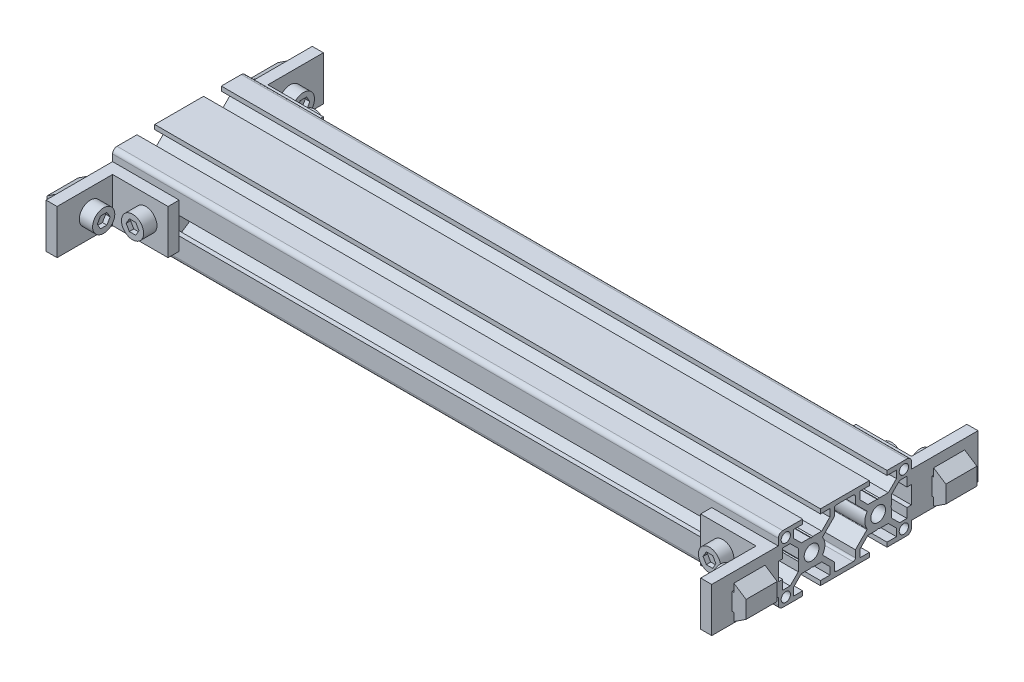
SolidWorks part; units mm, degrees
ref_plane "Front Plane" through (0, 0, 0) normal (0, 0, 1) x (1, 0, 0)
ref_plane "Top Plane" through (0, 0, 0) normal (0, 1, 0) x (1, 0, 0)
ref_plane "Right Plane" through (0, 0, 0) normal (1, 0, 0) x (0, 0, -1)
ref_plane "Plane1" through (300, 0, 0) normal (1, 0, 0) x (0, 0, -1)
ref_plane "Plane2" through (150, 0, 0) normal (1, 0, 0) x (0, 0, -1)
sketch "Sketch1" plane through (0, 0, 0) normal (1, 0, 0) x (0, 0, -1)
  line L0 (4.75, 8.8358) -> (4.75, 12)
  line L1 (3.75, 13) -> (-3.75, 13)
  line L2 (-4.75, 12) -> (-4.75, 8.8358)
  line L3 (-4.75, 8.8358) -> (-9.934, 3.6518)
  line L4 (-9.934, -3.6518) -> (-4.75, -8.8358)
  line L5 (-4.75, -8.8358) -> (-4.75, -12)
  line L6 (-3.75, -13) -> (3.75, -13)
  line L7 (4.75, -12) -> (4.75, -8.8358)
  line L8 (4.75, -8.8358) -> (9.934, -3.6518)
  line L9 (9.934, 3.6518) -> (4.75, 8.8358)
  line L10 (-11, -15) -> (11, -15)
  line L11 (11, -15) -> (11, -13)
  line L12 (11, -13) -> (6.75, -13)
  line L13 (6.75, -13) -> (6.75, -9.6642)
  line L14 (6.75, -9.6642) -> (10.4142, -6)
  line L15 (10.4142, -6) -> (14.4804, -6)
  line L16 (14.4804, -6) -> (15, -5.7)
  line L17 (15, -5.7) -> (15.5196, -6)
  line L18 (15.5196, -6) -> (19.5858, -6)
  line L19 (19.5858, -6) -> (23.25, -9.6642)
  line L20 (23.25, -9.6642) -> (23.25, -13)
  line L21 (23.25, -13) -> (19, -13)
  line L22 (19, -13) -> (19, -15)
  line L23 (19, -15) -> (28, -15)
  line L24 (30, -13) -> (30, -4)
  line L25 (30, -4) -> (28, -4)
  line L26 (28, -4) -> (28, -8.25)
  line L27 (28, -8.25) -> (24.6642, -8.25)
  line L28 (24.6642, -8.25) -> (21, -4.5858)
  line L29 (21, -4.5858) -> (21, -0.5196)
  line L30 (21, -0.5196) -> (20.7, 0)
  line L31 (20.7, 0) -> (21, 0.5196)
  line L32 (21, 0.5196) -> (21, 4.5858)
  line L33 (21, 4.5858) -> (24.6642, 8.25)
  line L34 (24.6642, 8.25) -> (28, 8.25)
  line L35 (28, 8.25) -> (28, 4)
  line L36 (28, 4) -> (30, 4)
  line L37 (30, 4) -> (30, 13)
  line L38 (28, 15) -> (19, 15)
  line L39 (19, 15) -> (19, 13)
  line L40 (19, 13) -> (23.25, 13)
  line L41 (23.25, 13) -> (23.25, 9.6642)
  line L42 (23.25, 9.6642) -> (19.5858, 6)
  line L43 (19.5858, 6) -> (15.5196, 6)
  line L44 (15.5196, 6) -> (15, 5.7)
  line L45 (15, 5.7) -> (14.4804, 6)
  line L46 (14.4804, 6) -> (10.4142, 6)
  line L47 (10.4142, 6) -> (6.75, 9.6642)
  line L48 (6.75, 9.6642) -> (6.75, 13)
  line L49 (6.75, 13) -> (11, 13)
  line L50 (11, 13) -> (11, 15)
  line L51 (11, 15) -> (-11, 15)
  line L52 (-11, 15) -> (-11, 13)
  line L53 (-11, 13) -> (-6.75, 13)
  line L54 (-6.75, 13) -> (-6.75, 9.6642)
  line L55 (-6.75, 9.6642) -> (-10.4142, 6)
  line L56 (-10.4142, 6) -> (-14.4804, 6)
  line L57 (-14.4804, 6) -> (-15, 5.7)
  line L58 (-15, 5.7) -> (-15.5196, 6)
  line L59 (-15.5196, 6) -> (-19.5858, 6)
  line L60 (-19.5858, 6) -> (-23.25, 9.6642)
  line L61 (-23.25, 9.6642) -> (-23.25, 13)
  line L62 (-23.25, 13) -> (-19, 13)
  line L63 (-19, 13) -> (-19, 15)
  line L64 (-19, 15) -> (-28, 15)
  line L65 (-30, 13) -> (-30, 4)
  line L66 (-30, 4) -> (-28, 4)
  line L67 (-28, 4) -> (-28, 8.25)
  line L68 (-28, 8.25) -> (-24.6642, 8.25)
  line L69 (-24.6642, 8.25) -> (-21, 4.5858)
  line L70 (-21, 4.5858) -> (-21, 0.5196)
  line L71 (-21, 0.5196) -> (-20.7, 0)
  line L72 (-20.7, 0) -> (-21, -0.5196)
  line L73 (-21, -0.5196) -> (-21, -4.5858)
  line L74 (-21, -4.5858) -> (-24.6642, -8.25)
  line L75 (-24.6642, -8.25) -> (-28, -8.25)
  line L76 (-28, -8.25) -> (-28, -4)
  line L77 (-28, -4) -> (-30, -4)
  line L78 (-30, -4) -> (-30, -13)
  line L79 (-28, -15) -> (-19, -15)
  line L80 (-19, -15) -> (-19, -13)
  line L81 (-19, -13) -> (-23.25, -13)
  line L82 (-23.25, -13) -> (-23.25, -9.6642)
  line L83 (-23.25, -9.6642) -> (-19.5858, -6)
  line L84 (-19.5858, -6) -> (-15.5196, -6)
  line L85 (-15.5196, -6) -> (-15, -5.7)
  line L86 (-15, -5.7) -> (-14.4804, -6)
  line L87 (-14.4804, -6) -> (-10.4142, -6)
  line L88 (-10.4142, -6) -> (-6.75, -9.6642)
  line L89 (-6.75, -9.6642) -> (-6.75, -13)
  line L90 (-6.75, -13) -> (-11, -13)
  line L91 (-11, -13) -> (-11, -15)
  arc A0 (28, -15) -> (30, -13) centre (28, -13) ccw
  arc A1 (30, 13) -> (28, 15) centre (28, 13) ccw
  arc A2 (-28, 15) -> (-30, 13) centre (-28, 13) ccw
  arc A3 (-30, -13) -> (-28, -15) centre (-28, -13) ccw
  circle A4 centre (-26.6, -11.6) radius 2.1
  circle A5 centre (-26.6, 11.6) radius 2.1
  circle A6 centre (-15, 0) radius 3.3235
  circle A7 centre (26.6, -11.6) radius 2.1
  circle A8 centre (15, 0) radius 3.3235
  circle A9 centre (26.6, 11.6) radius 2.1
  arc A10 (4.75, 12) -> (3.75, 13) centre (3.75, 12) ccw
  arc A11 (-3.75, 13) -> (-4.75, 12) centre (-3.75, 12) ccw
  arc A12 (-9.934, 3.6518) -> (-9.9732, 3.2759) centre (-9.7219, 3.4397) ccw
  arc A13 (-9.9732, -3.2759) -> (-9.9732, 3.2759) centre (-15, 0) ccw
  arc A14 (-9.9732, -3.2759) -> (-9.934, -3.6518) centre (-9.7219, -3.4397) ccw
  arc A15 (-4.75, -12) -> (-3.75, -13) centre (-3.75, -12) ccw
  arc A16 (3.75, -13) -> (4.75, -12) centre (3.75, -12) ccw
  arc A17 (9.934, -3.6518) -> (9.9732, -3.2759) centre (9.7219, -3.4397) ccw
  arc A18 (9.9732, 3.2759) -> (9.9732, -3.2759) centre (15, 0) ccw
  arc A19 (9.9732, 3.2759) -> (9.934, 3.6518) centre (9.7219, 3.4397) ccw
  point P106 (0, 0)
extrude "Boss-Extrude1" add sketch "Sketch1" along normal up to surface (300 mm away) up to plane "Plane1"
sketch "Sketch2" plane through (0, 0, 0) normal (0, 1, 0) x (1, 0, 0)
  line L0 (0, 60) -> (0, 30)
  line L1 (0, 30) -> (30, 30)
  line L2 (30, 30) -> (30, 35)
  line L3 (30, 35) -> (5, 35)
  line L4 (5, 35) -> (5, 60)
  line L5 (5, 60) -> (0, 60)
  dimension "FIX_1" = 30
  dimension "FIX_2" = 5
extrude "Boss-Extrude2" add sketch "Sketch2" along normal mid plane 20
ref_plane "Plane3" through (20, 0, 0) normal (1, 0, 0) x (0, 0, -1)
sketch "Sketch3" plane through (20, 0, 0) normal (1, 0, 0) x (0, 0, -1)
  line L0 (0, 0) -> (41, 0) construction
  line L1 (23, 0) -> (23, 3)
  line L2 (23, 3) -> (35, 3)
  line L3 (35, 3) -> (35, 5)
  line L4 (35, 5) -> (41, 5)
  line L5 (41, 5) -> (41, 0)
  line L6 (41, 0) -> (23, 0)
  dimension "FIX_7" = 6
  dimension "FIX_5" = 12
  dimension "FIX_6" = 6
  dimension "FIX_8" = 10
revolve "Revolve1" add sketch "Sketch3" angle 360 about L0
sketch "Sketch4" plane through (0, 0, -41) normal (0, 0, -1) x (-1, 0, 0)
  line L1 (-17.1132, 0) -> (-18.5566, 2.5)
  line L2 (-18.5566, 2.5) -> (-21.4434, 2.5)
  line L3 (-21.4434, 2.5) -> (-22.8868, 0)
  line L4 (-22.8868, 0) -> (-21.4434, -2.5)
  line L5 (-21.4434, -2.5) -> (-18.5566, -2.5)
  line L6 (-18.5566, -2.5) -> (-17.1132, 0)
  line L8 (49.5, 0) -> (-49.5, 0) construction
  circle A0 centre (-20, 0) radius 2.5 construction
  dimension "FIX_10" = 5
extrude "Cut-Extrude1" cut sketch "Sketch4" against normal blind 2
sketch "Sketch5" plane through (20, 0, 0) normal (1, 0, 0) x (0, 0, -1)
  line L0 (28, 7.5) -> (28, 3.9)
  line L1 (28, 3.9) -> (28.8, 3.9)
  line L2 (28.8, 3.9) -> (28.8, -3.9)
  line L3 (28.8, -3.9) -> (28, -3.9)
  line L4 (28, -3.9) -> (28, -7.5)
  line L5 (28, -7.5) -> (22.5, -3.9)
  line L6 (22.5, -3.9) -> (22.5, 3.9)
  line L7 (22.5, 3.9) -> (28, 7.5)
  line L8 (23, 0) -> (41, 0) construction
  line L10 (30, -13) -> (30, -4) construction
  dimension "FIX_12" = 1.2
  dimension "FIX_13" = 6.3
  dimension "FIX_14" = 0.8
  dimension "FIX_15" = 7.8
  dimension "FIX_16" = 15
extrude "Boss-Extrude3" add sketch "Sketch5" along normal mid plane 14
ref_plane "Plane4" through (0, 0, -45) normal (0, 0, -1) x (-1, 0, 0)
sketch "Sketch6" plane through (0, 0, -45) normal (0, 0, -1) x (-1, 0, 0)
  line L0 (7, 0) -> (-11, 0) construction
  line L1 (-30, 0) -> (-5, 0) construction
  line L2 (49.5, 0) -> (-49.5, 0) construction
  line L3 (-11, 0) -> (-11, 5)
  line L4 (-11, 5) -> (-5, 5)
  line L5 (-5, 5) -> (-5, 3)
  line L6 (-5, 3) -> (7, 3)
  line L7 (7, 3) -> (7, 0)
  line L8 (7, 0) -> (-11, 0)
  dimension "FIX_21" = 6
  dimension "FIX_19" = 12
  dimension "FIX_20" = 6
  dimension "FIX_22" = 10
revolve "Revolve2" add sketch "Sketch6" angle 360 about L0
sketch "Sketch7" plane through (11, 0, 0) normal (1, 0, 0) x (0, 0, -1)
  line L0 (60, 0) -> (30, 0) construction
  line L1 (47.8868, 0) -> (46.4434, 2.5)
  line L2 (46.4434, 2.5) -> (43.5566, 2.5)
  line L3 (43.5566, 2.5) -> (42.1132, 0)
  line L4 (42.1132, 0) -> (43.5566, -2.5)
  line L5 (43.5566, -2.5) -> (46.4434, -2.5)
  line L6 (46.4434, -2.5) -> (47.8868, 0)
  line L7 (49.5, 0) -> (-49.5, 0) construction
  circle A0 centre (45, 0) radius 2.5 construction
  dimension "FIX_24" = 5
extrude "Cut-Extrude2" cut sketch "Sketch7" against normal blind 2
sketch "Sketch8" plane through (0, 0, -45) normal (0, 0, -1) x (-1, 0, 0)
  line L0 (-11, 0) -> (7, 0) construction
  line L1 (7, -3) -> (7, 3) construction
  line L2 (1.2, -3.9) -> (1.2, 3.9)
  line L3 (1.2, 3.9) -> (2, 3.9)
  line L4 (2, 3.9) -> (2, 7.5)
  line L5 (2, 7.5) -> (7.5, 3.9)
  line L6 (7.5, 3.9) -> (7.5, -3.9)
  line L7 (7.5, -3.9) -> (2, -7.5)
  line L8 (2, -7.5) -> (2, -3.9)
  line L9 (2, -3.9) -> (1.2, -3.9)
  line L10 (0, -3) -> (0, 3) construction
  dimension "FIX_26" = 1.2
  dimension "FIX_27" = 6.3
  dimension "FIX_28" = 0.8
  dimension "FIX_29" = 7.8
  dimension "FIX_30" = 15
extrude "Boss-Extrude4" add sketch "Sketch8" along normal mid plane 14
mirror "Mirror1" about plane through (0, 0, 0) normal (0, 0, 1) of "Boss-Extrude4", "Cut-Extrude2", "Revolve2", "Boss-Extrude3", "Cut-Extrude1", "Revolve1", "Boss-Extrude2"
mirror "Mirror2" about plane through (150, 0, 0) normal (1, 0, 0) of "Boss-Extrude4", "Cut-Extrude2", "Revolve2", "Boss-Extrude3", "Cut-Extrude1", "Revolve1", "Boss-Extrude2", "Mirror1"
ref_plane "Plane5" through (-30, 0, 0) normal (1, 0, 0) x (0, 0, -1)
ref_plane "Plane6" through (330, 0, 0) normal (1, 0, 0) x (0, 0, -1)
